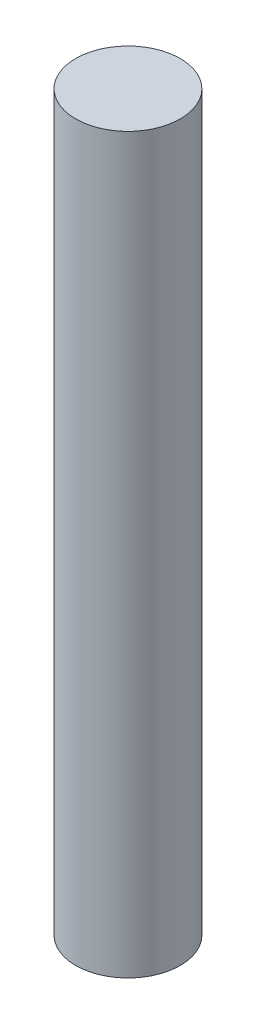
SolidWorks part; units mm, degrees
ref_plane "Alzado" through (0, 0, 0) normal (0, 0, 1) x (1, 0, 0)
ref_plane "Planta" through (0, 0, 0) normal (0, 1, 0) x (1, 0, 0)
ref_plane "Vista lateral" through (0, 0, 0) normal (1, 0, 0) x (0, 0, -1)
sketch "Sketch1" plane through (0, 0, 0) normal (0, 1, 0) x (1, 0, 0)
  circle A0 centre (0, 0) radius 4.85
  dimension "D1" = 9.7
extrude "Boss-Extrude1" add sketch "Sketch1" along normal mid plane 68
